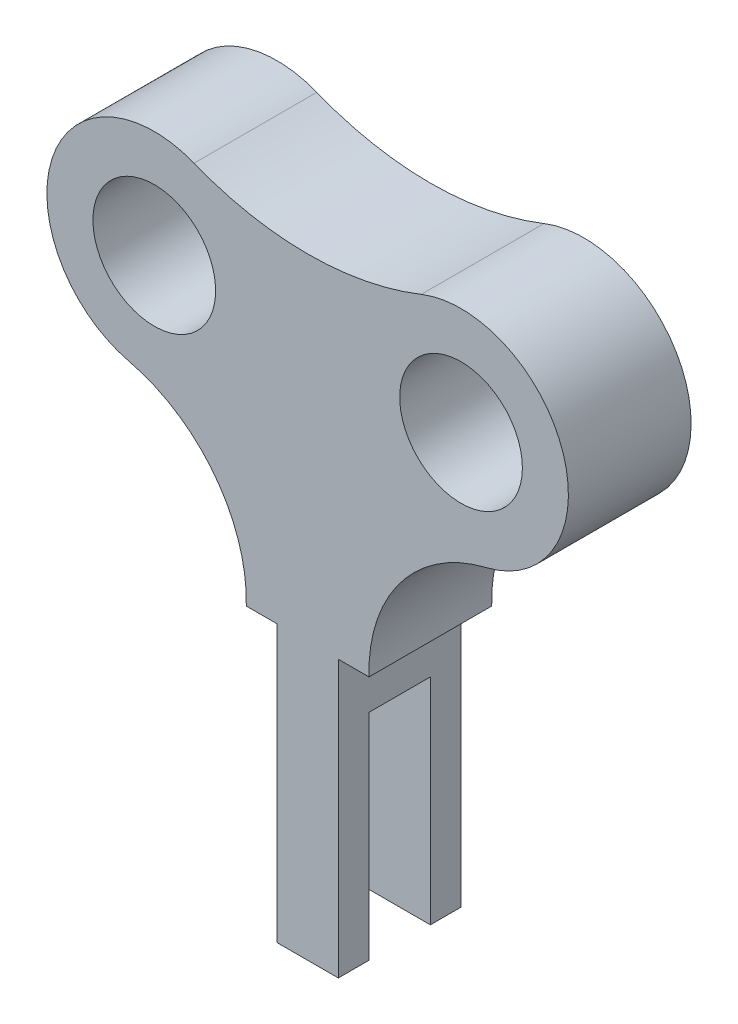
SolidWorks part; units mm, degrees
ref_plane "Front Plane" through (0, 0, 0) normal (0, 0, 1) x (1, 0, 0)
ref_plane "Top Plane" through (0, 0, 0) normal (0, 1, 0) x (1, 0, 0)
ref_plane "Right Plane" through (0, 0, 0) normal (1, 0, 0) x (0, 0, -1)
sketch "Sketch1" plane through (0, 0, 0) normal (0, 0, 1) x (1, 0, 0)
  line L0 (5, 22.5) -> (10, 22.5)
  line L2 (-5, 22.5) -> (-5, -22.5)
  line L3 (-5, -22.5) -> (5, -22.5)
  line L4 (5, 22.5) -> (5, -22.5)
  line L8 (-5, 22.5) -> (-10, 22.5)
  circle A0 centre (25, 64.5) radius 10
  circle A1 centre (-25, 64.5) radius 10
  arc A2 (-18.5185, 80.7555) -> (-29.1137, 47.4904) centre (-25, 64.5) ccw
  arc A3 (18.5185, 80.7555) -> (29.1137, 47.4904) centre (25, 64.5) cw
  arc A4 (-10, 22.5) -> (-29.1137, 47.4904) centre (-34.9905, 23.1909) ccw
  arc A5 (-18.5185, 80.7555) -> (18.5185, 80.7555) centre (0, 127.1997) ccw
  arc A6 (10, 22.5) -> (29.1137, 47.4904) centre (34.9905, 23.1909) cw
  point P0 (0, 0)
  dimension "D4" = 20
  dimension "D7" = 50
  dimension "D8" = 50
  dimension "D9" = 100
  dimension "D10" = 20
  dimension "D1" = 10
  dimension "D2" = 45
  dimension "D3" = 5
  dimension "D5" = 87
  dimension "D6" = 20
extrude "Boss-Extrude1" add sketch "Sketch1" along normal mid plane 20
sketch "Sketch2" plane through (-5, 0, 0) normal (-1, 0, 0) x (0, 0, 1)
  line L0 (10, -22.5) -> (-10, -22.5) construction
  line L1 (-5, -22.5) -> (5, -22.5)
  line L2 (-5, -22.5) -> (-5, 12.5)
  line L3 (-5, 12.5) -> (5, 12.5)
  line L4 (5, -22.5) -> (5, 12.5)
  line L5 (-10, 22.5) -> (-10, -22.5) construction
  dimension "D1" = 10
  dimension "D2" = 5
  dimension "D3" = 35
extrude "Cut-Extrude1" cut sketch "Sketch2" against normal up to surface (10 mm away) up to face at (5, 0, 0)
